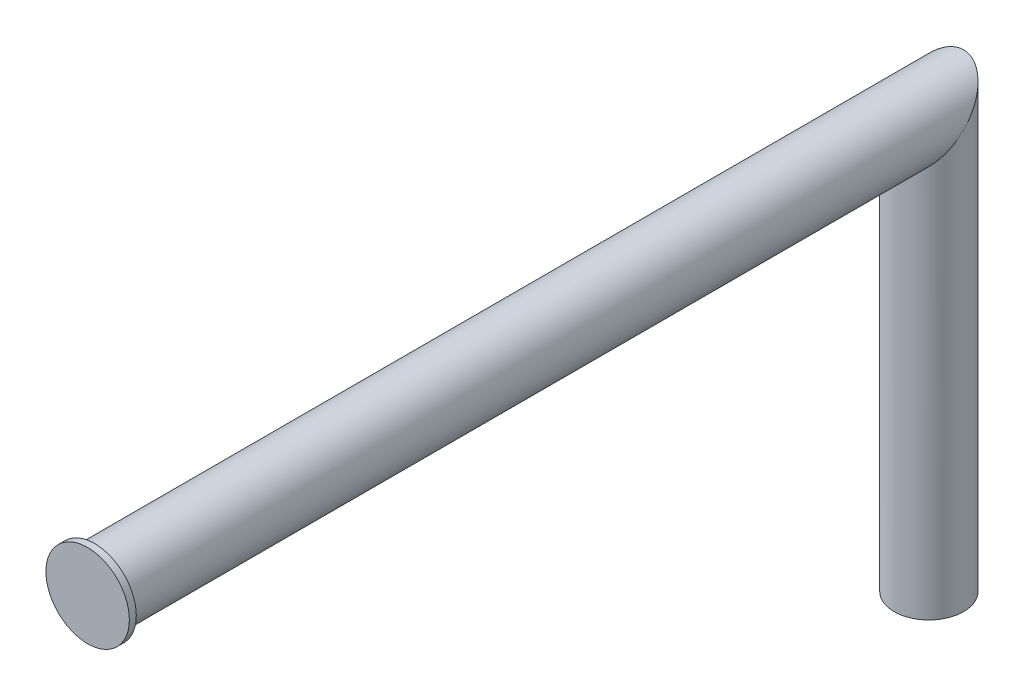
SolidWorks part; units mm, degrees
ref_plane "Front Plane" through (0, 0, 0) normal (0, 0, 1) x (1, 0, 0)
ref_plane "Top Plane" through (0, 0, 0) normal (0, 1, 0) x (1, 0, 0)
ref_plane "Right Plane" through (0, 0, 0) normal (1, 0, 0) x (0, 0, -1)
sketch "Sketch1" plane through (0, 0, 0) normal (1, 0, 0) x (0, 0, -1)
  line L0 (0, 0) -> (330.2, 0)
  line L1 (330.2, 0) -> (330.2, -152.4)
sketch "Sketch2" plane through (0, 0, 0) normal (0, 0, 1) x (1, 0, 0)
  circle A0 centre (0, 0) radius 12.7
sweep "Sweep1" add profiles "Sketch2" path "Sketch1"
sketch "Sketch6" plane through (0, 0, 0) normal (0, 0, 1) x (1, 0, 0)
  circle A0 centre (0, 0) radius 15.24
extrude "Boss-Extrude2" add sketch "Sketch6" against normal blind 25.4
sketch "Sketch7" plane through (0, 0, 0) normal (0, 0, 1) x (1, 0, 0)
  circle A0 centre (0, 0) radius 15.24 construction
  circle A1 centre (0, 0) radius 15.24
extrude "Cut-Extrude1" cut sketch "Sketch7" against normal blind 22.86
